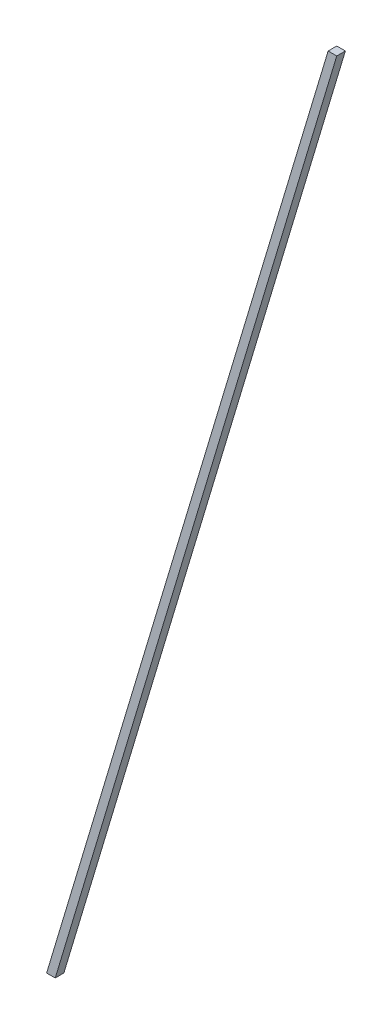
SolidWorks part; units mm, degrees
ref_plane "前视基准面" through (0, 0, 0) normal (0, 0, 1) x (1, 0, 0)
ref_plane "上视基准面" through (0, 0, 0) normal (0, 1, 0) x (1, 0, 0)
ref_plane "右视基准面" through (0, 0, 0) normal (1, 0, 0) x (0, 0, -1)
sketch "Model" plane through (0, 0, 0) normal (0, 0, 1) x (1, 0, 0)
  line L0 (166.5425, 169.098) -> (68.5366, -157.902)
  line L1 (68.5366, -157.902) -> (65.5366, -157.902)
  line L2 (166.5425, 169.098) -> (163.5425, 169.098)
  line L3 (163.5425, 169.098) -> (65.5366, -157.902)
extrude "凸台-拉伸1" add sketch "Model" along normal blind 3
